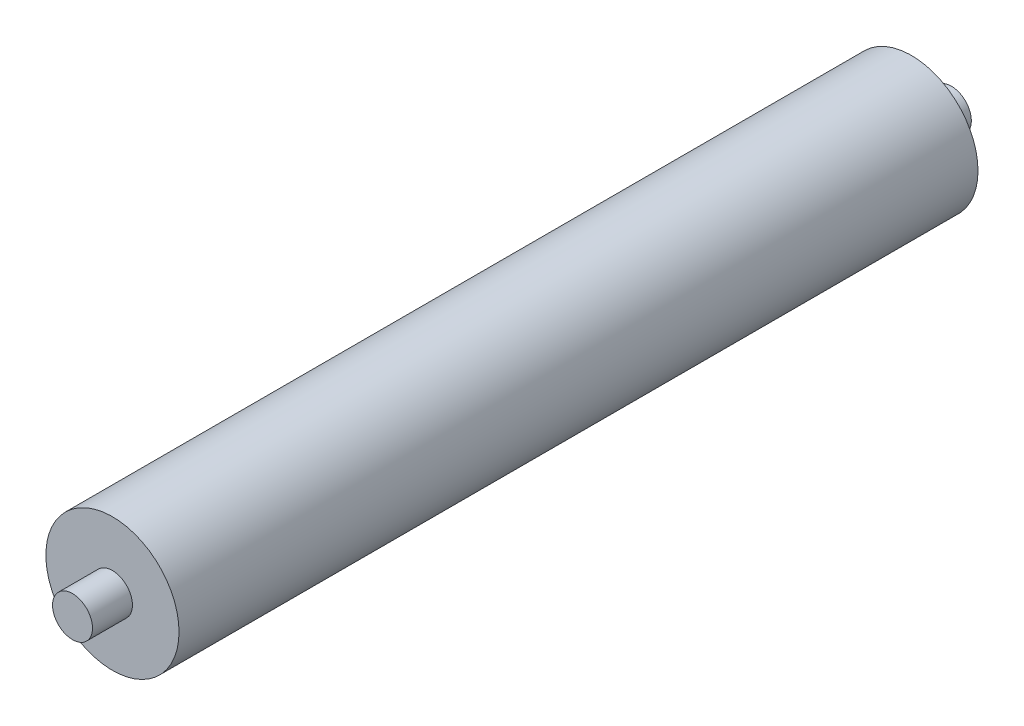
SolidWorks part; units mm, degrees
material "ABS"
ref_plane "Front Plane" through (0, 0, 0) normal (0, 0, 1) x (1, 0, 0)
ref_plane "Top Plane" through (0, 0, 0) normal (0, 1, 0) x (1, 0, 0)
ref_plane "Right Plane" through (0, 0, 0) normal (1, 0, 0) x (0, 0, -1)
sketch "Sketch1" plane through (0, 0, 0) normal (0, 0, 1) x (1, 0, 0)
  circle A0 centre (0, 0) radius 25
  dimension "D1" = 50
extrude "Boss-Extrude1" add sketch "Sketch1" along normal mid plane 300
shell "Shell1" thickness 5
sketch "Sketch2" plane through (0, 0, 150) normal (0, 0, 1) x (1, 0, 0)
  circle A0 centre (0, 0) radius 7.5
  dimension "D1" = 15
extrude "Boss-Extrude2" add sketch "Sketch2" along normal blind 15
mirror "Mirror1" about plane through (0, 0, 0) normal (0, 0, 1) of "Boss-Extrude2"
sketch "Sketch3" plane through (0, 0, 0) normal (1, 0, 0) x (0, 0, -1)
  line L0 (165, 0) -> (-165, 0) construction
  line L1 (-165, 7.5) -> (-165, -7.5) construction
  point P6 (0, 0)
